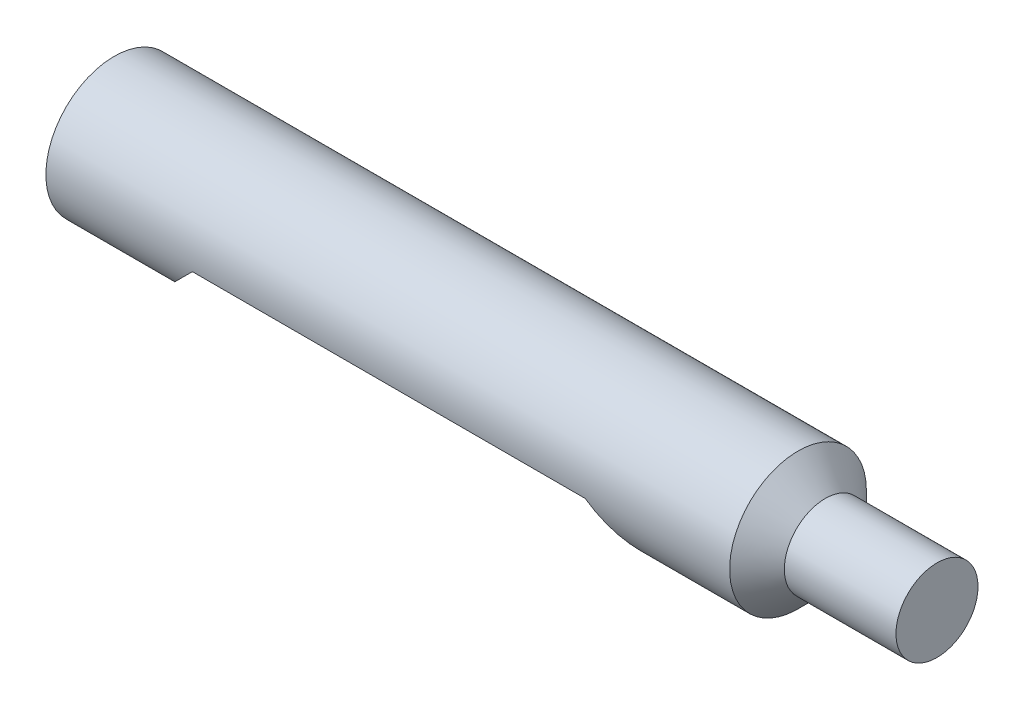
SolidWorks part; units mm, degrees
ref_plane "Front Plane" through (0, 0, 0) normal (0, 0, 1) x (1, 0, 0)
ref_plane "Top Plane" through (0, 0, 0) normal (0, 1, 0) x (1, 0, 0)
ref_plane "Right Plane" through (0, 0, 0) normal (1, 0, 0) x (0, 0, -1)
sketch "Sketch1" plane through (0, 0, 0) normal (0, 0, 1) x (1, 0, 0)
  line L0 (0, 0) -> (0, 5)
  line L1 (0, 5) -> (50, 5)
  line L2 (50, 5) -> (52, 3)
  line L3 (52, 3) -> (60.1622, 3)
  line L4 (60.1622, 3) -> (60.1622, 0)
  line L5 (60.1622, 0) -> (0, 0)
  dimension "D1" = 5
  dimension "D2" = 3
  dimension "D3" = 50
  dimension "D4" = 135
revolve "Revolve1" add sketch "Sketch1" angle 360 about L5
sketch "Sketch2" plane through (0, 0, 0) normal (0, 0, 1) x (1, 0, 0)
  line L0 (6.5, -5) -> (10.64, -0.86)
  line L1 (0, -5) -> (50, -5) construction
  line L2 (10.64, -0.86) -> (39.36, -0.86)
  line L3 (39.36, -0.86) -> (43.5, -5)
  line L4 (43.5, -5) -> (6.5, -5)
  line L9 (25, 17.263) -> (25, -8.5822) construction
  dimension "D1" = 37
  dimension "D2" = 45
  dimension "D3" = 25
  dimension "D4" = 18.5
  dimension "D5" = 0.86
  dimension "D6" = 45
extrude "Cut-Extrude1" cut sketch "Sketch2" against normal mid plane 35
